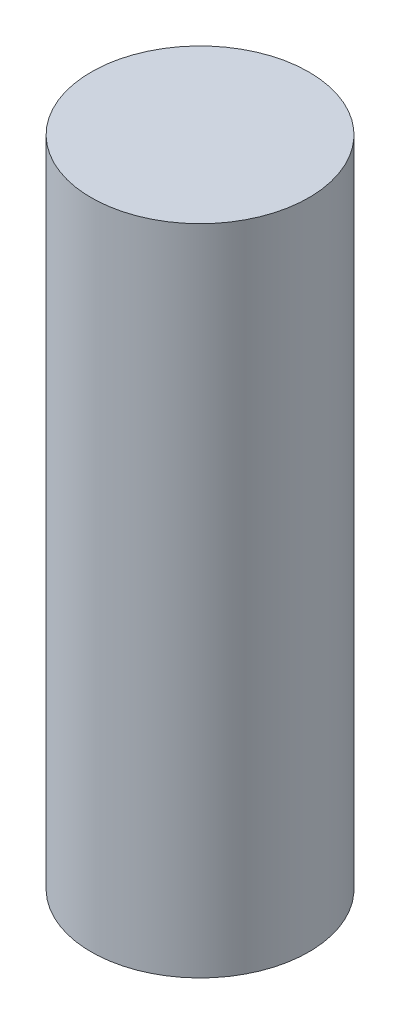
SolidWorks part; units mm, degrees
ref_plane "Front Plane" through (0, 0, 0) normal (0, 0, 1) x (1, 0, 0)
ref_plane "Top Plane" through (0, 0, 0) normal (0, 1, 0) x (1, 0, 0)
ref_plane "Right Plane" through (0, 0, 0) normal (1, 0, 0) x (0, 0, -1)
sketch "Sketch1" plane through (0, 0, 0) normal (0, 1, 0) x (1, 0, 0)
  circle A0 centre (0, 0) radius 3.175
  dimension "D1" = 6.35
extrude "Boss-Extrude1" add sketch "Sketch1" along normal blind 19.05
